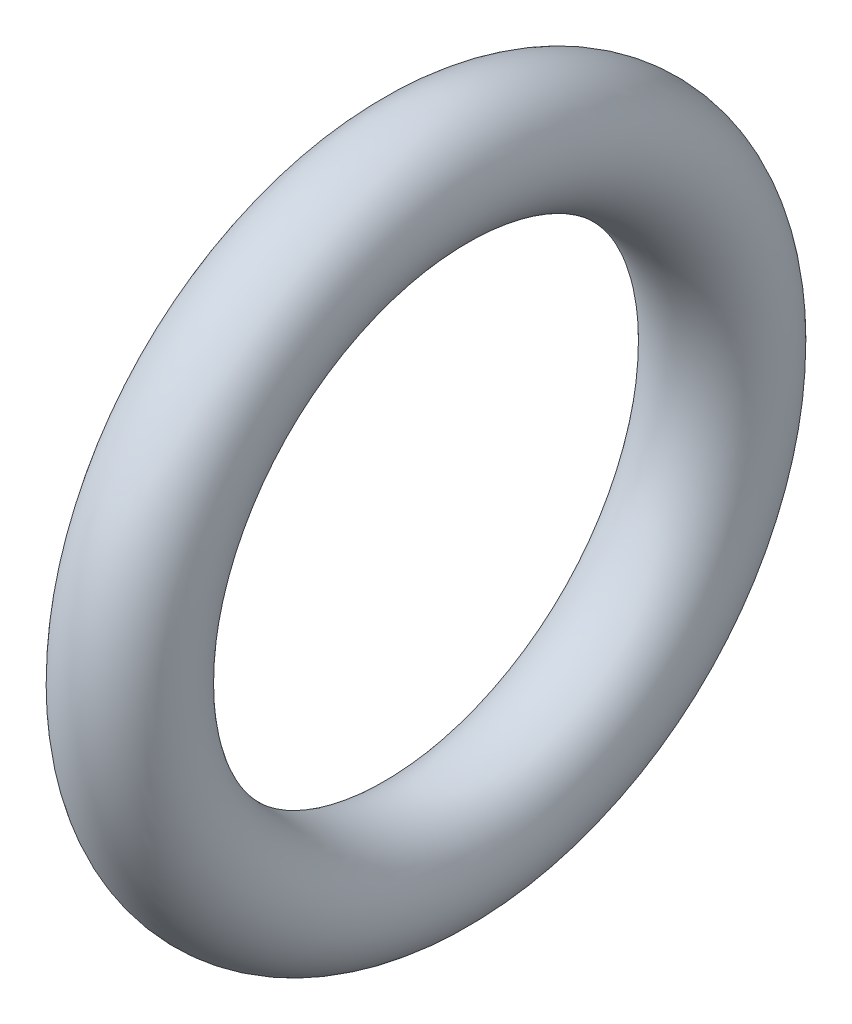
SolidWorks part; units mm, degrees
ref_plane "Plano frontal" through (0, 0, 0) normal (0, 0, 1) x (1, 0, 0)
ref_plane "Plano superior" through (0, 0, 0) normal (0, 1, 0) x (1, 0, 0)
ref_plane "Plano direito" through (0, 0, 0) normal (1, 0, 0) x (0, 0, -1)
sketch "Esboço1" plane through (0, 0, 0) normal (0, 0, 1) x (1, 0, 0)
  line L0 (0, 0) -> (7.1551, 0) construction
  line L1 (-1.5, 0) -> (-1.5, 5) construction
  line L2 (-1.5, 5) -> (-1, 5)
  line L3 (-1, 5) -> (-1, 4)
  line L4 (-1, 4) -> (1, 4)
  line L5 (1, 4) -> (1, 5)
  line L6 (1, 5) -> (1.5, 5)
  line L7 (1.5, 5) -> (1.5, 0) construction
  line L8 (1.5, 0) -> (-1.5, 0) construction
  line L9 (-1, 4) -> (1, 6) construction
  line L10 (-1, 4) -> (-1, 6) construction
  line L11 (1, 6) -> (-1, 6) construction
  line L12 (1, 6) -> (1, 4) construction
  line L13 (-1.5, 1) -> (1.5, 1)
  line L14 (-1.5, 5) -> (-1.5, 1)
  line L15 (1.5, 5) -> (1.5, 1)
  circle A0 centre (0, 5) radius 1
  point P5 (0, 5)
  point P18 (0, 0)
  dimension "D1" = 5
  dimension "D2" = 3
  dimension "D3" = 2
  dimension "D4" = 1
  dimension "D5" = 1
revolve "Revolução2" add sketch "Esboço1" angle 360 about L0
